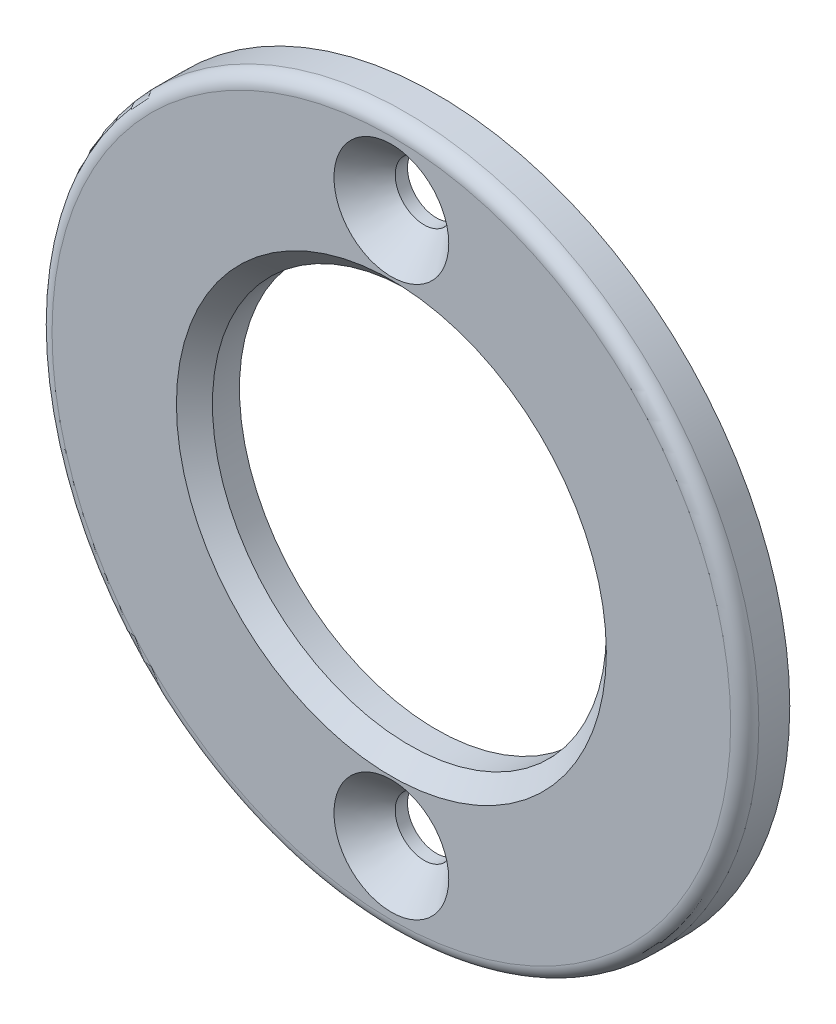
SolidWorks part; units mm, degrees
ref_plane "Front" through (0, 0, 0) normal (0, 0, 1) x (1, 0, 0)
ref_plane "Top" through (0, 0, 0) normal (0, 1, 0) x (1, 0, 0)
ref_plane "Right" through (0, 0, 0) normal (1, 0, 0) x (0, 0, -1)
sketch "Sketch1" plane through (0, 0, 0) normal (0, 0, 1) x (1, 0, 0)
  circle A0 centre (0, 0) radius 19.939
  dimension "D1" = 39.878
extrude "Boss-Extrude1" add sketch "Sketch1" along normal blind 2.54
hole_wizard "7/8 (0.875) Diameter Hole1" positions "Sketch3" profile "Sketch4" hole size "7/8" standard "ANSI Inch" end condition through all
sketch "Sketch3" plane through (0, 0, 2.54) normal (0, 0, 1) x (1, 0, 0)
  point P0 (0, 0)
  point P4 (0, 0)
sketch "Sketch4" plane through (0, 0, 2.54) normal (1, 0, 0) x (0, -1, 0)
  line L0 (0, 0) -> (0, 2.54)
  line L1 (0, 2.54) -> (11.1125, 2.54)
  line L2 (11.1125, 2.54) -> (11.1125, 0)
  line L5 (11.1125, 0) -> (0, 0)
  line L11 (0, -6.35) -> (0, 107.95) construction
  dimension "Thru Hole Dia." = 22.225
  dimension "Thru Hole Depth" = 2.54
hole_wizard "CSK for #4 Flat Head Socket Cap Screw1" positions "Sketch23" profile "Sketch24" countersink size "#4" standard "ANSI Inch" end condition through all
sketch "Sketch23" plane through (0, 0, 2.54) normal (0, 0, 1) x (1, 0, 0)
  line L1 (9.5872, 5.6189) -> (17.2022, 10.082) construction
  circle A0 centre (0, 0) radius 15.5258 construction
  circle A1 centre (0, 0) radius 11.1125 construction
  circle A2 centre (0, 0) radius 19.939 construction
  point P74 (0, 15.5258)
  point P76 (0, -15.5258)
  point P97 (13.3947, 7.8505)
  point P105 (0, 0)
sketch "Sketch24" plane through (0, 15.5258, 2.54) normal (1, 0, 0) x (0, -1, 0)
  line L0 (0, 0) -> (0, 2.54)
  line L1 (0, 2.54) -> (1.6319, 2.54)
  line L2 (1.6319, 2.54) -> (1.6319, 1.8481)
  line L3 (1.6319, 1.8481) -> (3.2385, 0)
  line L5 (3.2385, 0) -> (0, 0)
  line L6 (-1.632, 1.8481) -> (-3.2385, 0) construction
  line L11 (0, -6.35) -> (0, 107.95) construction
  dimension "Thru Hole Dia." = 3.2639
  dimension "Thru Hole Depth" = 2.54
  dimension "Near C'Sink Dia." = 6.477
  dimension "Near C'Sink Angle" = 82
chamfer "Chamfer1" distance 1.016 angle 45 1 edges at (11.1125, 0, 2.54)
fillet "Fillet1" radius 0.7937 1 edges at (19.939, 0, 2.54)
